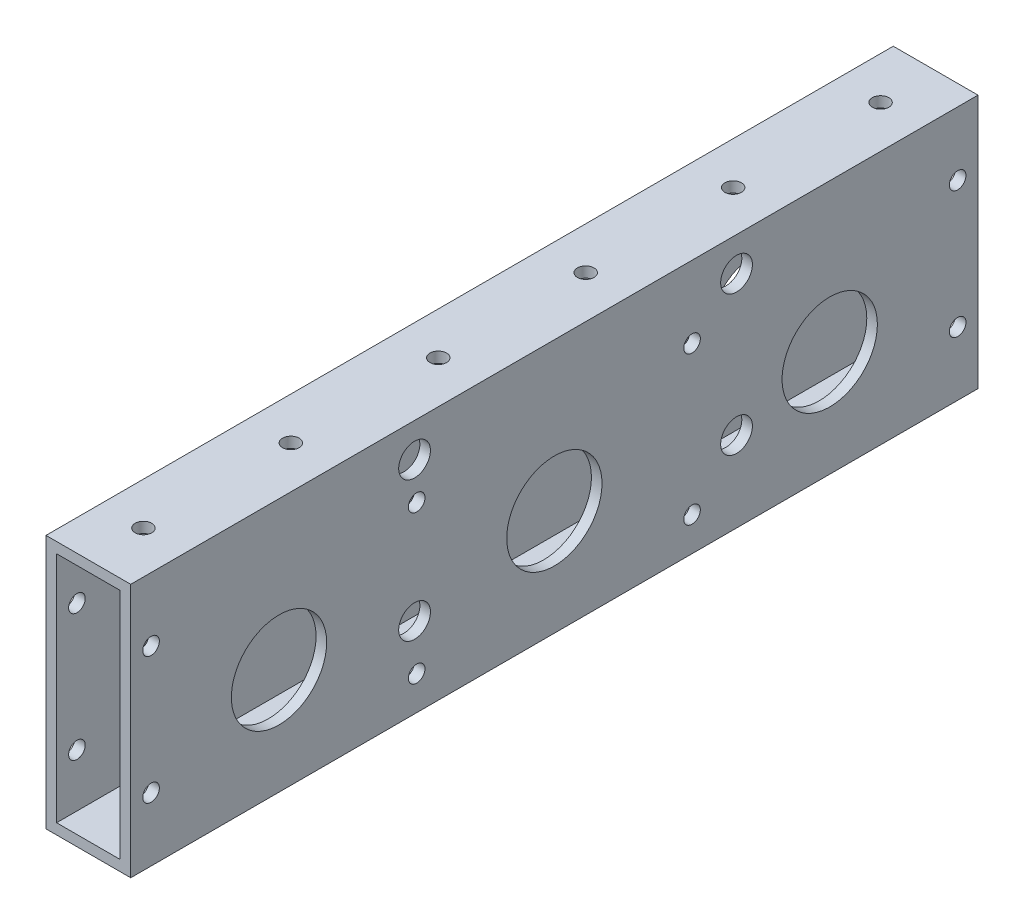
SolidWorks part; units mm, degrees
material "6061-T6 (SS)"
ref_plane "Front Plane" through (0, 0, 0) normal (0, 0, 1) x (1, 0, 0)
ref_plane "Top Plane" through (0, 0, 0) normal (0, 1, 0) x (1, 0, 0)
ref_plane "Right Plane" through (0, 0, 0) normal (1, 0, 0) x (0, 0, -1)
sketch "Sketch1" plane through (0, 0, 0) normal (1, 0, 0) x (0, 0, -1)
  line L1 (-127, 38.1) -> (127, 38.1)
  line L2 (-127, 38.1) -> (-127, -38.1)
  line L3 (-127, -38.1) -> (127, -38.1)
  line L4 (127, 38.1) -> (127, -38.1)
  line L5 (-127, 38.1) -> (127, -38.1) construction
  line L6 (-127, -38.1) -> (127, 38.1) construction
  point P0 (0, 0)
  dimension "D1" = 76.2
  dimension "D2" = 254
extrude "Boss-Extrude1" add sketch "Sketch1" along normal blind 25.4
shell "Shell1" thickness 3.175
sketch "Sketch2" plane through (25.4, 0, 0) normal (1, 0, 0) x (0, 0, -1)
  line L0 (-127, -38.1) -> (127, -38.1) construction
  line L1 (-82.55, -6.35) -> (0, -6.35) construction
  line L2 (-41.275, -27.94) -> (-41.275, -6.35) construction
  line L3 (0, -6.35) -> (82.55, -6.35) construction
  line L4 (41.275, -27.94) -> (41.275, -6.35) construction
  line L5 (127, 38.1) -> (-127, 38.1) construction
  line L6 (54.61, 27.94) -> (-41.91, 27.94) construction
  line L7 (54.61, 27.94) -> (54.61, -13.97) construction
  line L8 (54.61, -13.97) -> (-41.91, -13.97) construction
  line L9 (-41.91, 27.94) -> (-41.91, -13.97) construction
  line L10 (-127, -38.1) -> (127, -38.1) construction
  circle A0 centre (0, -6.35) radius 14.2875
  circle A1 centre (-82.55, -6.35) radius 14.2875
  circle A2 centre (82.55, -6.35) radius 14.2875
  circle A3 centre (-82.55, -6.35) radius 38.1 construction
  circle A4 centre (0, -6.35) radius 38.1 construction
  circle A5 centre (82.55, -6.35) radius 38.1 construction
  circle A6 centre (-41.275, -27.94) radius 6.35 construction
  circle A7 centre (41.275, -27.94) radius 6.35 construction
  circle A8 centre (-41.275, 16.51) radius 6.35 construction
  circle A9 centre (41.275, 16.51) radius 6.35 construction
  point P11 (0, 0)
  dimension "D1" = 28.575
  dimension "D5" = 76.2
  dimension "D7" = 12.7
  dimension "D2" = 31.75
  dimension "D3" = 82.55
  dimension "D4" = 82.55
  dimension "D6" = 0
  dimension "D8" = 10.16
  dimension "D9" = 44.45
  dimension "D10" = 41.91
  dimension "D11" = 96.52
  dimension "D12" = 10.16
  dimension "D13" = 24.13
extrude "Cut-Extrude1" cut sketch "Sketch2" against normal through all
sketch "Sketch3" plane through (25.4, 0, 0) normal (1, 0, 0) x (0, 0, -1)
  line L0 (-120.904, 19.05) -> (-120.904, -19.05) construction
  line L1 (-127, 38.1) -> (-127, -38.1) construction
  point P2 (-120.904, 0)
  point P3 (-127, 0)
  dimension "D1" = 38.1
  dimension "D2" = 6.096
hole_wizard "#10 Clearance Hole1" positions "Sketch4" profile "Sketch6" hole size "#10" standard "ANSI Inch" end condition through all
sketch "Sketch4" plane through (25.4, 0, 0) normal (1, 0, 0) x (0, 0, -1)
  point P0 (-120.904, 19.05)
  point P3 (-120.904, -19.05)
sketch "Sketch6" plane through (25.4, 19.05, 120.904) normal (0, 1, 0) x (0, 0, -1)
  line L0 (0, 0) -> (0, 25.4)
  line L1 (0, 25.4) -> (2.4892, 25.4)
  line L2 (2.4892, 25.4) -> (2.4892, 0)
  line L5 (2.4892, 0) -> (0, 0)
  line L11 (0, -6.35) -> (0, 107.95) construction
  dimension "Thru Hole Dia." = 4.9784
  dimension "Thru Hole Depth" = 25.4
mirror "Mirror1" about plane through (0, 0, 0) normal (0, 0, 1) of "#10 Clearance Hole1"
hole_wizard "#10 Clearance Hole2" positions "Sketch7" profile "Sketch8" hole size "#10" standard "ANSI Inch" end condition through all
sketch "Sketch7" plane through (25.4, 0, 0) normal (1, 0, 0) x (0, 0, -1)
  point P0 (-41.275, -27.94)
  point P3 (41.275, -27.94)
  point P7 (-41.275, 16.51)
  point P10 (41.275, 16.51)
sketch "Sketch8" plane through (25.4, -27.94, 41.275) normal (0, 1, 0) x (0, 0, -1)
  line L0 (0, 0) -> (0, 25.4)
  line L1 (0, 25.4) -> (2.4892, 25.4)
  line L2 (2.4892, 25.4) -> (2.4892, 0)
  line L5 (2.4892, 0) -> (0, 0)
  line L11 (0, -6.35) -> (0, 107.95) construction
  dimension "Thru Hole Dia." = 4.9784
  dimension "Thru Hole Depth" = 25.4
hole_wizard "3/8 (0.375) Diameter Hole1" positions "Sketch9" profile "Sketch10" hole size "3/8" standard "ANSI Inch"
sketch "Sketch9" plane through (0, 0, 0) normal (-1, 0, 0) x (0, 0, 1)
  point P0 (-41.275, -27.94)
  point P3 (41.275, -27.94)
  point P7 (41.275, 16.51)
  point P10 (-41.275, 16.51)
sketch "Sketch10" plane through (0, -27.94, -41.275) normal (0, 1, 0) x (0, 0, 1)
  line L0 (0, 0) -> (0, 15.5616)
  line L1 (0, 15.5616) -> (4.7625, 12.7)
  line L2 (4.7625, 12.7) -> (4.7625, 0)
  line L5 (4.7625, 0) -> (0, 0)
  line L10 (0, 15.5616) -> (-4.7625, 12.7) construction
  line L11 (0, -6.35) -> (0, 107.95) construction
  dimension "Hole Dia." = 9.525
  dimension "Hole Depth" = 12.7
  dimension "Drill Angle" = 118
hole_wizard "3/8 (0.375) Diameter Hole2" positions "Sketch11" profile "Sketch12" hole size "3/8" standard "ANSI Inch"
sketch "Sketch11" plane through (25.4, 0, 0) normal (1, 0, 0) x (0, 0, -1)
  point P0 (-41.91, 27.94)
  point P3 (54.61, 27.94)
  point P6 (54.61, -13.97)
  point P9 (-41.91, -13.97)
sketch "Sketch12" plane through (25.4, 27.94, 41.91) normal (0, 1, 0) x (0, 0, -1)
  line L0 (0, 0) -> (0, 15.5616)
  line L1 (0, 15.5616) -> (4.7625, 12.7)
  line L2 (4.7625, 12.7) -> (4.7625, 0)
  line L5 (4.7625, 0) -> (0, 0)
  line L10 (0, 15.5616) -> (-4.7625, 12.7) construction
  line L11 (0, -6.35) -> (0, 107.95) construction
  dimension "Hole Dia." = 9.525
  dimension "Hole Depth" = 12.7
  dimension "Drill Angle" = 118
hole_wizard "#10 Clearance Hole3" positions "Sketch13" profile "Sketch14" hole size "#10" standard "ANSI Inch"
sketch "Sketch13" plane through (0, 0, 0) normal (-1, 0, 0) x (0, 0, 1)
  point P0 (41.91, 27.94)
  point P3 (-54.61, 27.94)
  point P6 (-54.61, -13.97)
  point P9 (41.91, -13.97)
sketch "Sketch14" plane through (0, 27.94, 41.91) normal (0, 1, 0) x (0, 0, 1)
  line L0 (0, 0) -> (0, 14.1957)
  line L1 (0, 14.1957) -> (2.4892, 12.7)
  line L2 (2.4892, 12.7) -> (2.4892, 0)
  line L5 (2.4892, 0) -> (0, 0)
  line L10 (0, 14.1957) -> (-2.4892, 12.7) construction
  line L11 (0, -6.35) -> (0, 107.95) construction
  dimension "Hole Dia." = 4.9784
  dimension "Hole Depth" = 12.7
  dimension "Drill Angle" = 118
sketch "Sketch15" plane through (0, -38.1, 0) normal (0, -1, 0) x (1, 0, 0)
  line L0 (12.7, 110.49) -> (12.7, -110.49) construction
  line L1 (25.4, 127) -> (25.4, -127) construction
  line L2 (25.4, 127) -> (0, 127) construction
  point P2 (25.4, 0)
  point P3 (12.7, 0)
  point P7 (12.7, 127)
  dimension "D1" = 16.51
hole_wizard "#10 Clearance Hole4" positions "Sketch16" profile "Sketch17" hole size "#10" standard "ANSI Inch" end condition through all
sketch "Sketch16" plane through (0, -38.1, 0) normal (0, -1, 0) x (-1, 0, 0)
  point P0 (-12.7, -110.49)
  point P3 (-12.7, 110.49)
sketch "Sketch17" plane through (12.7, -38.1, 110.49) normal (1, 0, 0) x (0, 0, -1)
  line L0 (0, 0) -> (0, 76.2)
  line L1 (0, 76.2) -> (2.4892, 76.2)
  line L2 (2.4892, 76.2) -> (2.4892, 0)
  line L5 (2.4892, 0) -> (0, 0)
  line L11 (0, -6.35) -> (0, 107.95) construction
  dimension "Thru Hole Dia." = 4.9784
  dimension "Thru Hole Depth" = 76.2
sketch "Sketch18" plane through (0, 38.1, 0) normal (0, 1, 0) x (1, 0, 0)
  line L0 (25.4, 127) -> (0, 127) construction
  line L1 (25.4, 127) -> (25.4, -127) construction
  point P0 (12.7, 127)
  point P1 (12.7, 66.294)
  point P4 (25.4, 0)
  point P6 (12.7, 22.098)
  dimension "D1" = 44.196
  dimension "D2" = 22.098
hole_wizard "#10 Clearance Hole5" positions "Sketch19" profile "Sketch21" hole size "#10" standard "ANSI Inch" end condition through all
sketch "Sketch19" plane through (0, 38.1, 0) normal (0, 1, 0) x (1, 0, 0)
  point P0 (12.7, 66.294)
  point P4 (12.7, 22.098)
sketch "Sketch21" plane through (12.7, 38.1, -66.294) normal (1, 0, 0) x (0, 0, 1)
  line L0 (0, 0) -> (0, 76.2)
  line L1 (0, 76.2) -> (2.4892, 76.2)
  line L2 (2.4892, 76.2) -> (2.4892, 0)
  line L5 (2.4892, 0) -> (0, 0)
  line L11 (0, -6.35) -> (0, 107.95) construction
  dimension "Thru Hole Dia." = 4.9784
  dimension "Thru Hole Depth" = 76.2
mirror "Mirror2" about plane through (0, 0, 0) normal (0, 0, 1) of "#10 Clearance Hole5"
